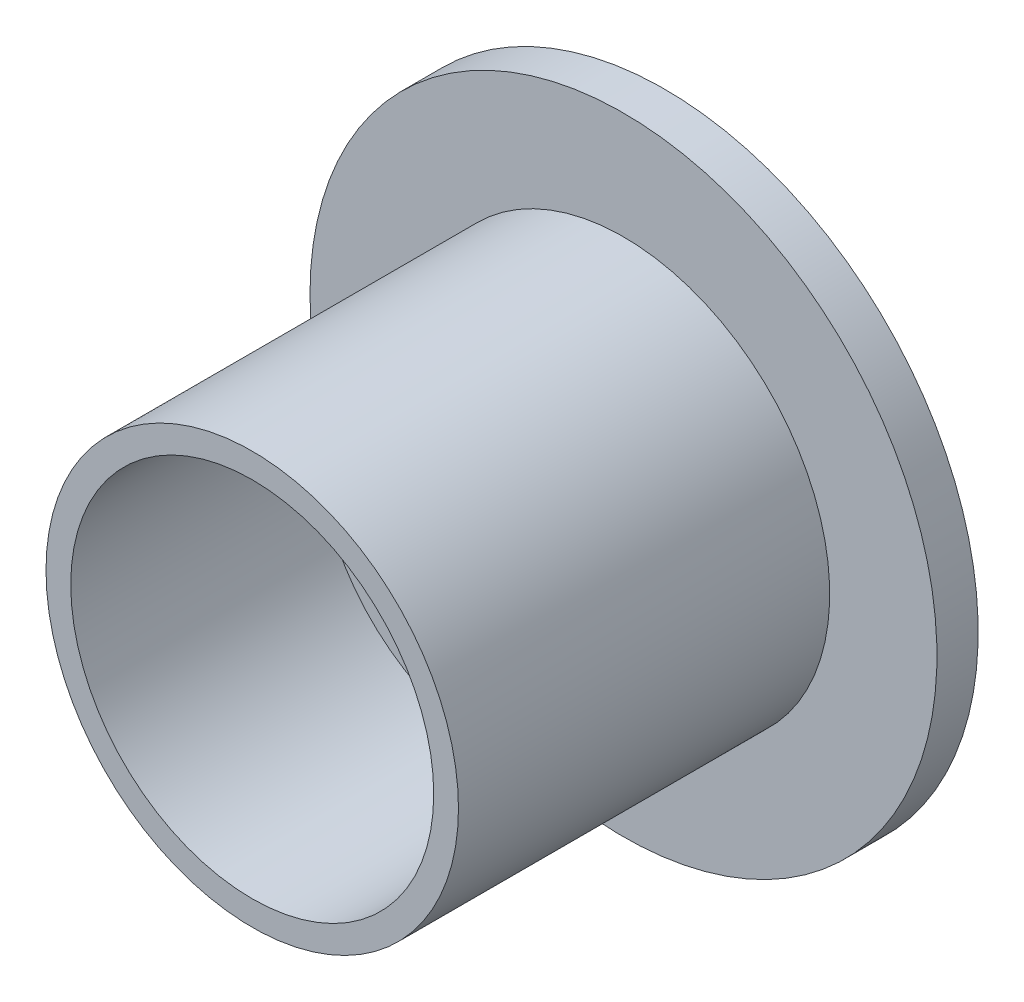
SolidWorks part; units mm, degrees
ref_plane "Front Plane" through (0, 0, 0) normal (0, 0, 1) x (1, 0, 0)
ref_plane "Top Plane" through (0, 0, 0) normal (0, 1, 0) x (1, 0, 0)
ref_plane "Right Plane" through (0, 0, 0) normal (1, 0, 0) x (0, 0, -1)
ref_axis "Axis1" through (0, 0, -2.5) along (0, 0, 1)
sketch "Sketch1" plane through (0, 0, 0) normal (0, 0, 1) x (1, 0, 0)
  circle A0 centre (0, 0) radius 25
  dimension "D1" = 50
extrude "Boss-Extrude1" add sketch "Sketch1" along normal blind 50
sketch "Sketch4" plane through (0, 0, 0) normal (1, 0, 0) x (0, 0, -1)
  line L1 (0, 38) -> (-5, 38)
  line L2 (0, 38) -> (0, 25)
  line L3 (0, 25) -> (-5, 25)
  line L4 (-5, 38) -> (-5, 25)
  dimension "D1" = 5
  dimension "D2" = 13
revolve "Revolve1" add sketch "Sketch4" angle 360 about axis through (0, 0, -2.5) along (0, 0, 1)
sketch "Sketch2" plane through (0, 0, 0) normal (0, 0, -1) x (-1, 0, 0)
  circle A3 centre (0, 0) radius 22
extrude "Cut-Extrude1" cut sketch "Sketch2" against normal through all draft 5
sketch "Sketch3" plane through (0, 0, 50) normal (0, 0, 1) x (1, 0, 0)
  circle A2 centre (0, 0) radius 22
  circle A3 centre (0, 0) radius 22
  dimension "D1" = 3
extrude "Cut-Extrude2" cut sketch "Sketch3" against normal blind 30
